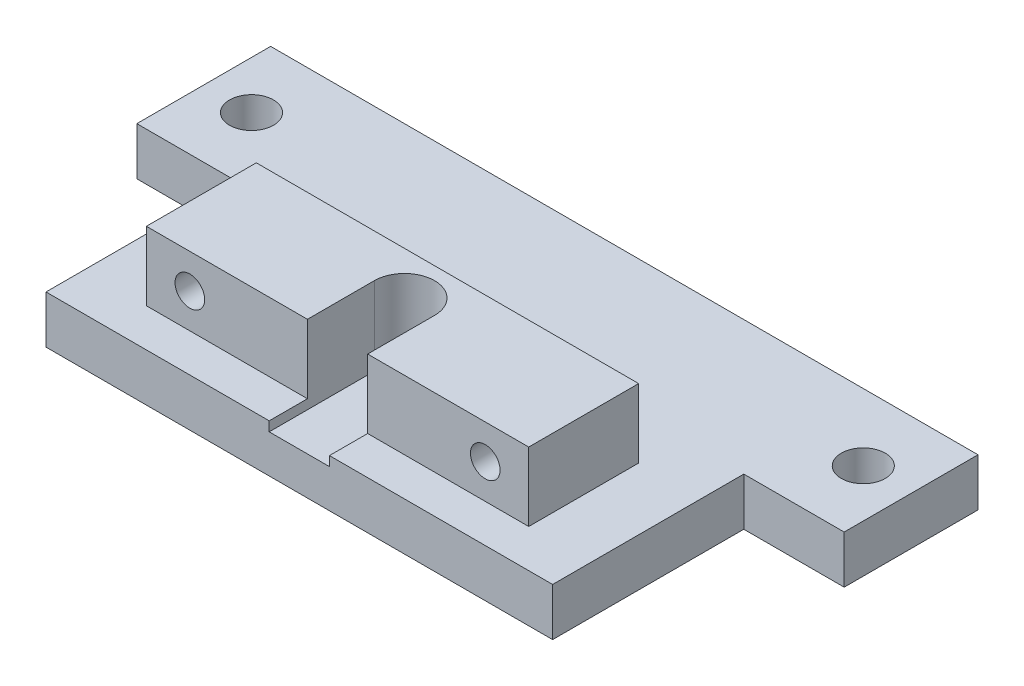
SolidWorks part; units mm, degrees
ref_plane "Front Plane" through (0, 0, 0) normal (0, 0, 1) x (1, 0, 0)
ref_plane "Top Plane" through (0, 0, 0) normal (0, 1, 0) x (1, 0, 0)
ref_plane "Right Plane" through (0, 0, 0) normal (1, 0, 0) x (0, 0, -1)
sketch "Sketch1" plane through (0, 0, 0) normal (0, 1, 0) x (1, 0, 0)
  line L0 (37, 14) -> (37, 0) construction
  line L1 (0, 0) -> (74, 0)
  line L2 (0, 0) -> (0, 14)
  line L3 (0, 14) -> (74, 14)
  line L4 (74, 0) -> (74, 14)
  line L5 (10, 14) -> (10, 0) construction
  line L6 (10.5, 0) -> (10.5, -20)
  line L7 (10.5, -20) -> (63.5, -20)
  line L8 (63.5, 0) -> (63.5, -20)
  circle A0 centre (5, 7) radius 2.3
  circle A1 centre (69, 7) radius 2.3
  point P10 (37, 7)
  point P18 (37, -20)
  dimension "D3" = 4.6
  dimension "D1" = 74
  dimension "D2" = 14
  dimension "D4" = 5
  dimension "D5" = 10
  dimension "D6" = 1
  dimension "D7" = 20
extrude "Boss-Extrude1" add sketch "Sketch1" along normal blind 5.2 contours L1 L4 L3 L2 A0 A1 | L8 L1 L6 L7
sketch "Sketch2" plane through (0, 5.2, 0) normal (0, 1, 0) x (1, 0, 0)
  line L2 (37, 14) -> (37, -9)
  line L3 (0, 14) -> (74, 14) construction
  line L4 (33.85, -9) -> (33.85, -20)
  line L5 (10.5, -20) -> (63.5, -20) construction
  line L6 (40.15, -9) -> (40.15, -20)
  line L7 (40.15, -20) -> (33.85, -20)
  arc A0 (40.15, -9) -> (33.85, -9) centre (37, -9) ccw
  dimension "D1" = 6.3
  dimension "D2" = 23
extrude "Cut-Extrude1" cut sketch "Sketch2" against normal blind 1
sketch "Sketch3" plane through (0, 5.2, 0) normal (0, 1, 0) x (1, 0, 0)
  line L0 (33.85, -9) -> (33.85, -16)
  line L1 (17, -16) -> (33.85, -16)
  line L2 (17, -16) -> (17, -4.5)
  line L3 (17, -4.5) -> (57, -4.5)
  line L4 (57, -16) -> (57, -4.5)
  line L5 (40.15, -9) -> (40.15, -16)
  line L6 (0, 14) -> (74, 14) construction
  line L7 (40.15, -16) -> (57, -16)
  arc A0 (40.15, -9) -> (33.85, -9) centre (37, -9) ccw
  circle A1 centre (37, -9) radius 3.15 construction
  point P6 (37, -9)
  point P7 (37, -4.5)
  dimension "D1" = 18.5
  dimension "D2" = 40
  dimension "D3" = 11.5
extrude "Boss-Extrude2" add sketch "Sketch3" along normal blind 7.2
sketch "Sketch5" plane through (0, 0, 4.5) normal (0, 0, -1) x (-1, 0, 0)
  line L0 (-57, 12.4) -> (-57, 5.2) construction
  line L1 (-17, 12.4) -> (-17, 5.2) construction
  circle A0 centre (-52.45, 8.8) radius 1.55
  circle A1 centre (-21.55, 8.8) radius 1.55
  point P4 (-20, 8.8)
  point P5 (-54, 8.8)
  point P11 (-57, 8.8)
  dimension "D1" = 3.1
  dimension "D2" = 3.1
  dimension "D3" = 3
  dimension "D4" = 3
extrude "Cut-Extrude2" cut sketch "Sketch5" against normal through all
sketch "Sketch6" plane through (0, 0, 0) normal (-1, 0, 0) x (0, 0, 1)
  line L0 (-14, 0) -> (-14, 0.2)
  line L1 (-14, 5.2) -> (-14, 0) construction
  line L2 (-14, 0.2) -> (20, 0.2)
  line L4 (20, 0.2) -> (20, 0)
  line L5 (20, 0) -> (-14, 0)
  line L6 (20, 5.2) -> (20, 0) construction
  dimension "D1" = 0.2
extrude "Cut-Extrude3" cut sketch "Sketch6" against normal through all
ref_plane "Plane1" through (0, 0, 0) normal (0, 0, 1) x (1, 0, 0)
